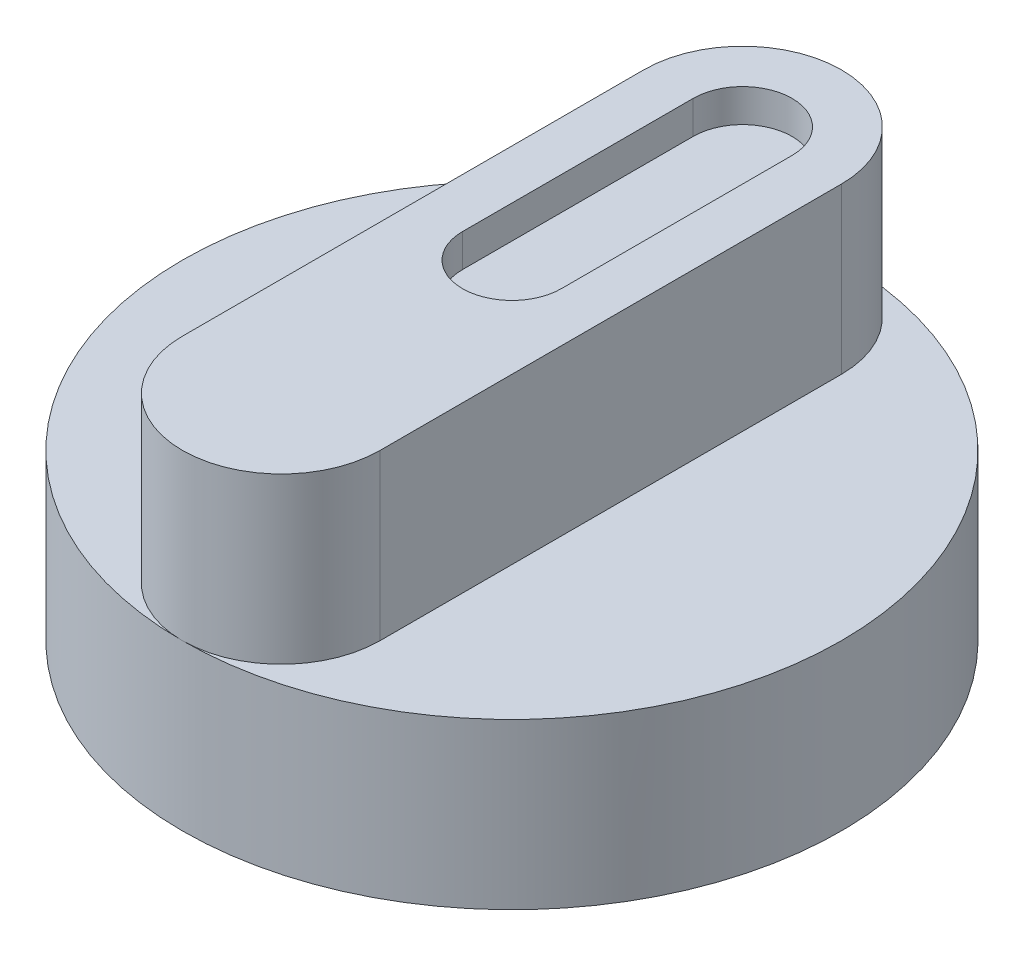
SolidWorks part; units mm, degrees
ref_plane "정면" through (0, 0, 0) normal (0, 0, 1) x (1, 0, 0)
ref_plane "윗면" through (0, 0, 0) normal (0, 1, 0) x (1, 0, 0)
ref_plane "우측면" through (0, 0, 0) normal (1, 0, 0) x (0, 0, -1)
sketch "스케치1" plane through (0, 0, 0) normal (0, 1, 0) x (1, 0, 0)
  circle A0 centre (0, 0) radius 20
  dimension "D1" = 40
extrude "보스-돌출1" add sketch "스케치1" along normal blind 10
sketch "스케치2" plane through (0, 10, 0) normal (0, 1, 0) x (1, 0, 0)
  line L0 (0, 14) -> (0, -14) construction
  line L1 (6, 14) -> (6, -14)
  line L2 (-6, 14) -> (-6, -14)
  arc A0 (6, 14) -> (-6, 14) centre (0, 14) ccw
  arc A1 (-6, -14) -> (6, -14) centre (0, -14) ccw
  circle A2 centre (0, 0) radius 20 construction
  point P2 (0, 0)
  dimension "D1" = 12
extrude "보스-돌출2" add sketch "스케치2" along normal blind 10
sketch "스케치3" plane through (0, 20, 0) normal (0, 1, 0) x (1, 0, 0)
  line L0 (0, 14) -> (0, 0) construction
  line L1 (3, 14) -> (3, 0)
  line L2 (-3, 14) -> (-3, 0)
  arc A0 (3, 14) -> (-3, 14) centre (0, 14) ccw
  arc A1 (-3, 0) -> (3, 0) centre (0, 0) ccw
  arc A4 (6, 14) -> (0, 20) centre (0, 14) ccw construction
  point P2 (0, 7)
  dimension "D1" = 3
extrude "컷-돌출1" cut sketch "스케치3" against normal blind 2
